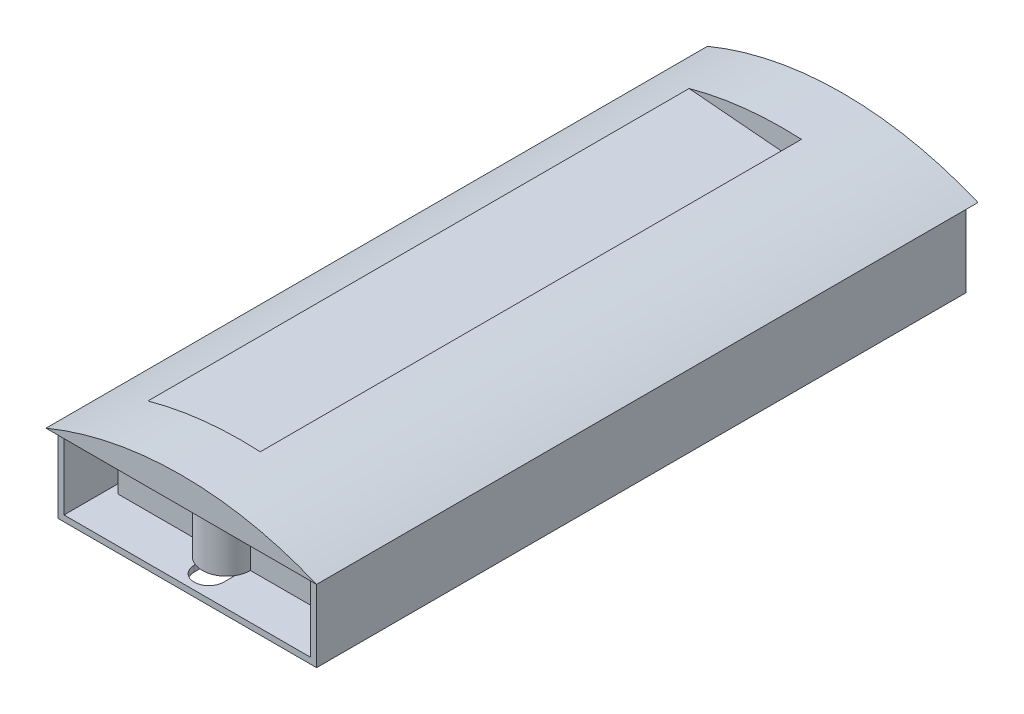
SolidWorks part; units mm, degrees
ref_plane "前视基准面" through (0, 0, 0) normal (0, 0, 1) x (1, 0, 0)
ref_plane "上视基准面" through (0, 0, 0) normal (0, 1, 0) x (1, 0, 0)
ref_plane "右视基准面" through (0, 0, 0) normal (1, 0, 0) x (0, 0, -1)
sketch "草图1" plane through (0, 0, 0) normal (0, 0, 1) x (1, 0, 0)
  line L0 (0, 0) -> (45, 0)
  arc A0 (0, 0) -> (45, 0) centre (22.5, -54) cw
  point P3 (22.5, 4.5)
  dimension "D1" = 45
  dimension "D2" = 4.5
extrude "凸台-拉伸1" add sketch "草图1" along normal blind 110
sketch "草图2" plane through (0, 0, 0) normal (0, -1, 0) x (-1, 0, 0)
  line L0 (0, -55) -> (-45, -55) construction
  line L1 (0, -110) -> (0, 0) construction
  line L2 (-45, -110) -> (-45, 0) construction
  line L3 (-22.5, -7.5) -> (-22.5, -102.5) construction
  line L4 (-4.5, -7.5) -> (-40.5, -7.5)
  line L5 (-4.5, -7.5) -> (-4.5, -102.5)
  line L6 (-4.5, -102.5) -> (-40.5, -102.5)
  line L7 (-40.5, -7.5) -> (-40.5, -102.5)
  line L8 (-4.5, -7.5) -> (-40.5, -102.5) construction
  line L9 (-4.5, -102.5) -> (-40.5, -7.5) construction
  line L10 (-18.5, -7.5) -> (-18.5, -102.5)
  line L11 (-26.5, -7.5) -> (-26.5, -102.5)
  arc A0 (-18.5, -7.5) -> (-26.5, -7.5) centre (-22.5, -7.5) ccw
  arc A1 (-26.5, -102.5) -> (-18.5, -102.5) centre (-22.5, -102.5) ccw
  point P6 (-22.5, -55)
  point P13 (-22.5, -55)
  point P18 (-22.5, -106.5)
  point P19 (-22.5, -3.5)
  dimension "D1" = 36
  dimension "D2" = 95
  dimension "D3" = 8
  dimension "D4" = 103
extrude "凸台-拉伸2" add sketch "草图2" along normal blind 11 contours L4 L10 L6 L5 | L4 L11 L6 L10 | L6 A1 | L11 L4 L7 L6 | L4 A0
sketch "草图3" plane through (0, -11, 0) normal (0, -1, 0) x (1, 0, 0)
  circle A0 centre (22.5, 102.5) radius 1.6
  circle A1 centre (22.5, 7.5) radius 1.6
  dimension "D1" = 3.2
extrude "切除-拉伸1" cut sketch "草图3" against normal blind 11
ref_plane "基准面1" through (0, -12, 0) normal (0, -1, 0) x (-1, 0, 0)
sketch "草图4" plane through (0, -12, 0) normal (0, -1, 0) x (-1, 0, 0)
  line L0 (-40.5, -55) -> (-4.5, -55) construction
  line L1 (-40.5, -7.5) -> (-40.5, -102.5) construction
  line L2 (-4.5, -7.5) -> (-4.5, -102.5) construction
  line L3 (-22.5, -4.6) -> (-22.5, -10.4) construction
  line L4 (-44, -109) -> (-1, -109)
  line L5 (-44, -109) -> (-44, -1)
  line L6 (-44, -1) -> (-1, -1)
  line L7 (-1, -109) -> (-1, -1)
  line L8 (-44, -109) -> (-1, -1) construction
  line L9 (-44, -1) -> (-1, -109) construction
  line L10 (-20.05, -4.6) -> (-20.05, -10.4)
  line L11 (-24.95, -4.6) -> (-24.95, -10.4)
  line L12 (-22.5, -105.4) -> (-22.5, -99.6) construction
  line L13 (-20.05, -105.4) -> (-20.05, -99.6)
  line L14 (-24.95, -105.4) -> (-24.95, -99.6)
  arc A0 (-20.05, -4.6) -> (-24.95, -4.6) centre (-22.5, -4.6) ccw
  arc A1 (-24.95, -10.4) -> (-20.05, -10.4) centre (-22.5, -10.4) ccw
  arc A2 (-20.05, -105.4) -> (-24.95, -105.4) centre (-22.5, -105.4) cw
  arc A3 (-24.95, -99.6) -> (-20.05, -99.6) centre (-22.5, -99.6) cw
  point P6 (-22.5, -55)
  point P13 (-22.5, -7.5)
  point P21 (-22.5, -102.5)
  dimension "D1" = 43
  dimension "D2" = 108
  dimension "D3" = 4.9
  dimension "D4" = 5.8
extrude "凸台-拉伸3" add sketch "草图4" along normal blind 1 separate body
sketch "草图5" plane through (0, 0, 109) normal (0, 0, 1) x (1, 0, 0)
  line L0 (22.5, -13) -> (22.5, -16.1921) construction
  line L1 (1, -13) -> (2, -13)
  line L2 (1, -13) -> (1, -1)
  line L3 (1, -1) -> (2, -1)
  line L4 (2, -13) -> (2, -1)
  line L5 (44, -13) -> (1, -13) construction
  line L6 (43, -13) -> (43, -1)
  line L7 (44, -1) -> (43, -1)
  line L8 (44, -13) -> (44, -1)
  line L9 (44, -13) -> (43, -13)
  dimension "D1" = 1
  dimension "D2" = 12
extrude "凸台-拉伸4" add sketch "草图5" against normal up to surface (108 mm away) up to face at (22.5, -12.5, 1)
ref_plane "基准面2" through (0, 0, 55) normal (0, 0, -1) x (-1, 0, 0)
sketch "草图6" plane through (0, 0, 55) normal (0, 0, -1) x (-1, 0, 0)
  line L0 (-25.6355, 4.4159) -> (-28.8797, 3.1149)
  line L3 (-21.709, 7.7542) -> (-25.6355, 4.4159)
  line L4 (-28.8797, 0.4972) -> (-5.3884, 2.5313)
  line L5 (-21.709, 7.7542) -> (-5.3884, 2.5313)
  arc A0 (0, 0) -> (-45, 0) centre (-22.5, -54) ccw construction
  arc A1 (-28.8797, 0.4972) -> (-28.8797, 3.1149) centre (-28.3548, 1.8061) cw
extrude "切除-拉伸2" cut sketch "草图6" against normal blind 45 and the other way blind 45
